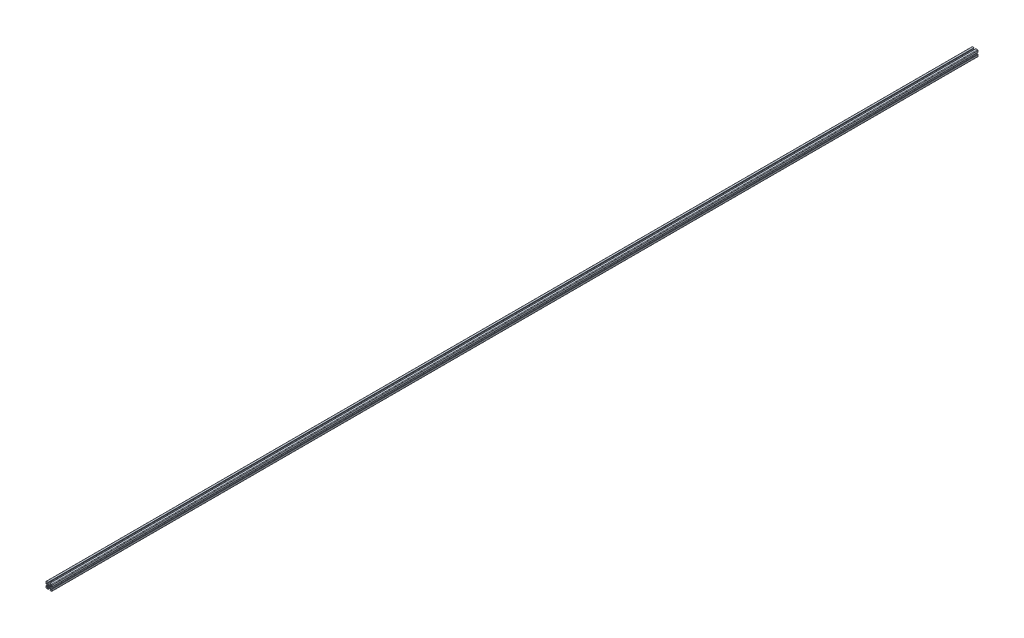
SolidWorks part; units mm, degrees
ref_plane "Front Plane" through (0, 0, 0) normal (0, 0, 1) x (1, 0, 0)
ref_plane "Top Plane" through (0, 0, 0) normal (0, 1, 0) x (1, 0, 0)
ref_plane "Right Plane" through (0, 0, 0) normal (1, 0, 0) x (0, 0, -1)
sketch "Sketch2" plane through (0, 0, 0) normal (0, 0, 1) x (1, 0, 0)
  line L0 (0, 10) -> (0, -10) construction
  line L1 (-10, 0) -> (10, 0) construction
  line L2 (2.5, -10) -> (10, -10)
  line L3 (10, -10) -> (10, -2.5)
  line L4 (2.5, -10) -> (2.5, -7.9246)
  line L5 (2.5, -7.9246) -> (6.4571, -7.9246)
  line L6 (6.4571, -7.9246) -> (2.1325, -3.6)
  line L7 (0, 0) -> (10, -10) construction
  line L8 (10, -2.5) -> (7.9246, -2.5)
  line L9 (7.9246, -2.5) -> (7.9246, -6.4571)
  line L10 (7.9246, -6.4571) -> (3.6, -2.1325)
  line L11 (5.7623, -4.2948) -> (4.2948, -5.7623) construction
  circle A0 centre (0, 0) radius 2.15
  arc A1 (5.25, -7.9246) -> (5.6036, -7.0711) centre (5.25, -7.4246) ccw construction
  point P8 (0, -3.6)
  point P16 (5.0286, -5.0286)
  dimension "Center Hole Diameter" = 4.3
  dimension "D3" = 0.5
  dimension "Rail Height" = 20
  dimension "Rail Width" = 20
  dimension "T-Slot Width" = 5
  dimension "Slot Depth" = 6.4
  dimension "Slot Inner Width" = 11.5
sketch "Sketch3" plane through (0, 0, 0) normal (1, 0, 0) x (0, 0, -1)
  line L0 (-1524, -10) -> (1524, -10) construction
  line L1 (-1498.6, 0) -> (1498.6, 0) construction
  line L2 (0, 10) -> (0, -10) construction
  line L3 (0, 10) -> (0, -10) construction
  point P6 (-1498.6, 0)
  point P8 (1498.6, 0)
  dimension "Length" = 3048
  dimension "D1" = 25.4
sketch "Sketch4" plane through (0, 0, 0) normal (0, 0, 1) x (1, 0, 0)
  line L0 (3, -10) -> (8.25, -10)
  line L1 (2.5, -10) -> (10, -10) construction
  line L2 (2.5, -10) -> (2.5, -7.9246) construction
  line L3 (2.5, -7.9246) -> (6.4571, -7.9246) construction
  line L4 (2.5, -8.4246) -> (2.5, -9.5)
  line L5 (3, -7.9246) -> (5.25, -7.9246)
  line L6 (0, -3.6) -> (0.8898, -3.6)
  line L7 (6.4571, -7.9246) -> (2.1325, -3.6) construction
  line L8 (3.0112, -4.4787) -> (5.6036, -7.0711)
  line L9 (10, -10) -> (10, -2.5) construction
  line L10 (7.9246, -6.4571) -> (3.6, -2.1325) construction
  line L11 (7.9246, -2.5) -> (7.9246, -6.4571) construction
  line L12 (7.9246, -5.25) -> (7.9246, -3)
  line L13 (10, -2.5) -> (7.9246, -2.5) construction
  line L14 (8.4246, -2.5) -> (9.5, -2.5)
  line L15 (10, -3) -> (10, -8.25)
  line L16 (7.0711, -5.6036) -> (4.4787, -3.0112)
  line L17 (3.6, 0) -> (3.6, -0.8898)
  line L18 (-10, 0) -> (10, 0) construction
  line L19 (0, -3.6) -> (0, -2.15)
  line L20 (0, 10) -> (0, -10) construction
  line L21 (3.6, 0) -> (2.15, 0)
  arc A0 (2.5, -9.5) -> (3, -10) centre (3, -9.5) ccw
  arc A1 (5.25, -7.9246) -> (5.6036, -7.0711) centre (5.25, -7.4246) ccw construction
  arc A2 (2.5, -8.4246) -> (3, -7.9246) centre (3, -8.4246) cw
  arc A3 (5.25, -7.9246) -> (5.6036, -7.0711) centre (5.25, -7.4246) ccw
  arc A4 (0.8898, -3.6) -> (3.0112, -4.4787) centre (0.8898, -6.6) cw
  arc A5 (8.25, -10) -> (10, -8.25) centre (8.25, -8.25) ccw
  arc A6 (7.0711, -5.6036) -> (7.9246, -5.25) centre (7.4246, -5.25) ccw
  arc A7 (7.9246, -3) -> (8.4246, -2.5) centre (8.4246, -3) cw
  arc A8 (9.5, -2.5) -> (10, -3) centre (9.5, -3) cw
  arc A9 (4.4787, -3.0112) -> (3.6, -0.8898) centre (6.6, -0.8898) cw
  circle A10 centre (0, 0) radius 2.15 construction
  arc A11 (0, -2.15) -> (2.15, 0) centre (0, 0) ccw
  dimension "D1" = 1.75
  dimension "D2" = 3
extrude "Boss-Extrude1" add sketch "Sketch4" along normal mid plane 3048
mirror "Mirror1" about plane through (0, 0, 0) normal (1, 0, 0) of bodies 134
mirror "Mirror2" about plane through (0, 0, 0) normal (0, 1, 0) of bodies 135
equation "\"D3@Sketch2\"=\"T-Slot Width@Sketch2\"*0.1"
equation "\"D1@Sketch4\"=\"D3@Sketch2\"*3.5"
equation "\"D2@Sketch4\"=\"D3@Sketch2\"*6"
equation "\"D1@Boss-Extrude1\"=\"Length@Sketch3\""
